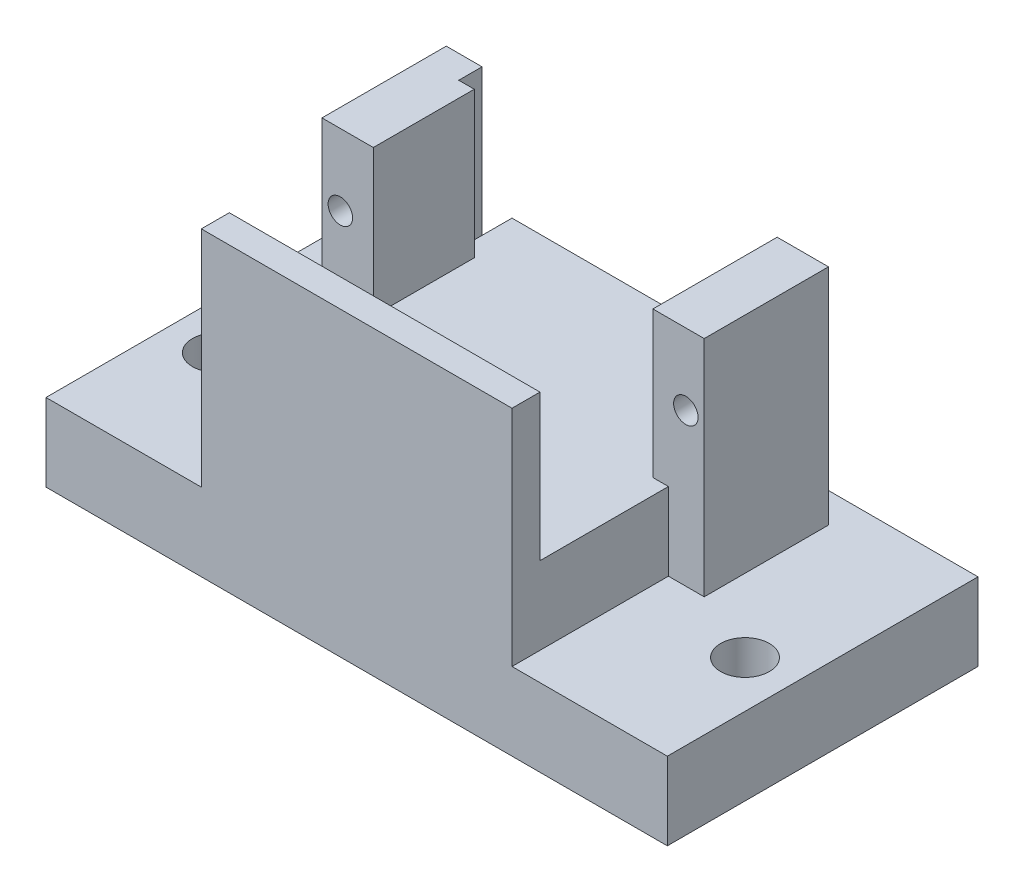
SolidWorks part; units mm, degrees
ref_plane "Front Plane" through (0, 0, 0) normal (0, 0, 1) x (1, 0, 0)
ref_plane "Top Plane" through (0, 0, 0) normal (0, 1, 0) x (1, 0, 0)
ref_plane "Right Plane" through (0, 0, 0) normal (1, 0, 0) x (0, 0, -1)
sketch "Sketch1" plane through (0, 0, 0) normal (0, 1, 0) x (1, 0, 0)
  line L1 (-12.7, -12.7) -> (12.7, -12.7)
  line L2 (-12.7, -12.7) -> (-12.7, 12.7)
  line L3 (-12.7, 12.7) -> (12.7, 12.7)
  line L4 (12.7, -12.7) -> (12.7, 12.7)
  line L5 (-12.7, -12.7) -> (12.7, 12.7) construction
  line L6 (-12.7, 12.7) -> (12.7, -12.7) construction
  point P0 (0, 0)
  dimension "D1" = 25.4
  dimension "D2" = 25.4
extrude "Boss-Extrude1" add sketch "Sketch1" along normal blind 12.7
sketch "Sketch2" plane through (-12.7, 0, 0) normal (-1, 0, 0) x (0, 0, 1)
  line L0 (-12.7, 6.35) -> (12.7, 6.35)
  line L1 (-12.7, 12.7) -> (-12.7, 0) construction
  line L2 (12.7, 12.7) -> (12.7, 0) construction
  line L7 (-12.7, 0) -> (12.7, 0)
  line L8 (12.7, 0) -> (12.7, 12.7)
  line L9 (12.7, 12.7) -> (-12.7, 12.7)
  line L10 (-12.7, 12.7) -> (-12.7, 0)
  line L11 (-12.7, 0) -> (12.7, 0)
  line L12 (12.7, 0) -> (12.7, 6.35)
  line L14 (-12.7, 6.35) -> (-12.7, 0)
  dimension "D1" = 0
extrude "Boss-Extrude2" add sketch "Sketch2" along normal blind 12.7
mirror "Mirror1" about plane through (0, 0, 0) normal (1, 0, 0) of "Boss-Extrude2"
sketch "Sketch3" plane through (0, 6.35, 0) normal (0, 1, 0) x (1, 0, 0)
  line L0 (-10.85, -1.1) -> (10.85, -1.1) construction
  line L1 (10.85, -1.1) -> (10.85, 10.25) construction
  line L2 (10.85, 10.25) -> (-10.85, 10.25) construction
  line L3 (-10.85, 10.25) -> (-10.85, -1.1) construction
  line L4 (-15.625, 10.25) -> (-11.2071, 10.25) construction
  line L5 (-11.2071, 10.25) -> (11.2071, 10.25) construction
  line L6 (11.2071, 10.25) -> (15.625, 10.25) construction
  line L7 (15.625, 10.25) -> (15.625, 12.7) construction
  line L8 (15.625, 12.7) -> (-15.625, 12.7) construction
  line L9 (-15.625, 12.7) -> (-15.625, 10.25) construction
  line L10 (-10.85, -1.1) -> (10.85, -1.1)
  line L11 (10.85, -1.1) -> (10.85, 10.25)
  line L12 (10.85, 10.25) -> (-10.85, 10.25)
  line L13 (-10.85, 10.25) -> (-10.85, -1.1)
  line L14 (-15.625, 10.25) -> (-11.2071, 10.25)
  line L15 (-11.2071, 10.25) -> (11.2071, 10.25)
  line L16 (11.2071, 10.25) -> (15.625, 10.25)
  line L17 (15.625, 10.25) -> (15.625, 12.7)
  line L18 (15.625, 12.7) -> (-15.625, 12.7)
  line L19 (-15.625, 12.7) -> (-15.625, 10.25)
ref_plane "Plane1" through (0, 24.638, 0) normal (0, 1, 0) x (1, 0, 0)
sketch "Sketch6" plane through (0, 6.35, 0) normal (0, 1, 0) x (1, 0, 0)
  line L0 (-12.7, -12.7) -> (-12.7, 12.7) construction
  line L1 (-15.625, 10.25) -> (-12.7, 10.25)
  line L2 (-15.625, 10.25) -> (-15.625, 0.09)
  line L3 (-15.625, 0.09) -> (-12.7, 0.09)
  line L4 (-12.7, 10.25) -> (-12.7, 0.09)
  line L5 (0, -13.5509) -> (0, 13.5509) construction
  line L6 (12.7, 10.25) -> (12.7, 0.09)
  line L7 (15.625, 10.25) -> (12.7, 10.25)
  line L8 (15.625, 10.25) -> (15.625, 0.09)
  line L9 (15.625, 0.09) -> (12.7, 0.09)
  dimension "D1" = 10.16
extrude "Boss-Extrude3" add sketch "Sketch6" along normal up to surface (18.288 mm away) up to plane "Plane1"
sketch "Sketch8" plane through (0, 12.7, 0) normal (0, 1, 0) x (1, 0, 0)
  line L0 (-12.7, 0.09) -> (-12.7, 10.25) construction
  line L1 (-11.43, 8.345) -> (-12.7, 8.345)
  line L2 (-11.43, 8.345) -> (-11.43, 0.09)
  line L3 (-11.43, 0.09) -> (-12.7, 0.09)
  line L4 (-12.7, 8.345) -> (-12.7, 0.09)
  line L5 (11.43, 10.25) -> (12.7, 10.25)
  line L6 (11.43, 10.25) -> (11.43, 0.09)
  line L7 (11.43, 0.09) -> (12.7, 0.09)
  line L8 (12.7, 10.25) -> (12.7, 0.09)
  line L9 (-12.7, 0.09) -> (-12.7, 10.25) construction
  line L10 (15.625, 10.25) -> (12.7, 10.25) construction
  line L11 (15.625, 10.25) -> (12.7, 10.25) construction
  line M2 (12.7, 0.09) -> (12.7, 10.25)
  line M6 (-12.7, 10.25) -> (-12.7, 0.09)
  dimension "D1" = 1.27
  dimension "D2" = 1.27
extrude "Boss-Extrude4" add sketch "Sketch8" along normal up to surface (11.938 mm away) contours L3 L2 L1 M6 | L6 L7 L5 M2 up to plane "Plane1"
sketch "Sketch9" plane through (0, 12.7, 0) normal (0, 1, 0) x (1, 0, 0)
  line L0 (12.7, -12.7) -> (12.7, 0.09) construction
  line L1 (-12.7, -12.7) -> (12.7, -12.7)
  line L2 (-12.7, -12.7) -> (-12.7, -10.414)
  line L3 (-12.7, -10.414) -> (12.7, -10.414)
  line L4 (12.7, -12.7) -> (12.7, -10.414)
  line M10 (-12.7, 0.09) -> (-12.7, -12.7)
  line M11 (-12.7, -12.7) -> (12.7, -12.7)
  line M12 (12.7, -12.7) -> (12.7, 0.09)
  dimension "D1" = 2.286
extrude "Boss-Extrude5" add sketch "Sketch9" along normal up to surface (11.938 mm away) contours L3 M10 M11 M12 up to face at (-13.2517, 24.638, -6.2283)
sketch "Sketch10" plane through (0, 6.35, 0) normal (0, 1, 0) x (1, 0, 0)
  line L0 (25.4, -12.7) -> (25.4, 12.7) construction
  line L1 (25.4, -12.7) -> (12.7, -12.7) construction
  line L2 (0, -13.5509) -> (0, 13.5509) construction
  circle A0 centre (21.59, -2.54) radius 1.9939
  circle A1 centre (-21.59, -2.54) radius 1.9939
  dimension "D1" = 3.9878
  dimension "D2" = 3.81
  dimension "D3" = 10.16
extrude "Cut-Extrude1" cut sketch "Sketch10" against normal through all contours A0 | A1
sketch "Sketch11" plane through (0, 0, -10.25) normal (0, 0, -1) x (-1, 0, 0)
  arc A0 (-14.991, 18.3) -> (-14.991, 19.3) centre (-14.125, 18.8) ccw construction
  arc A1 (14.991, 19.3) -> (14.991, 18.3) centre (14.125, 18.8) ccw construction
  arc A2 (-14.991, 18.3) -> (-14.991, 19.3) centre (-14.125, 18.8) ccw
  arc A3 (14.991, 19.3) -> (14.991, 18.3) centre (14.125, 18.8) ccw
  circle A4 centre (-14.125, 18.8) radius 1
  circle A5 centre (14.125, 18.8) radius 1
extrude "Cut-Extrude2" cut sketch "Sketch11" against normal through all contours A3 A5 | A2 A4
